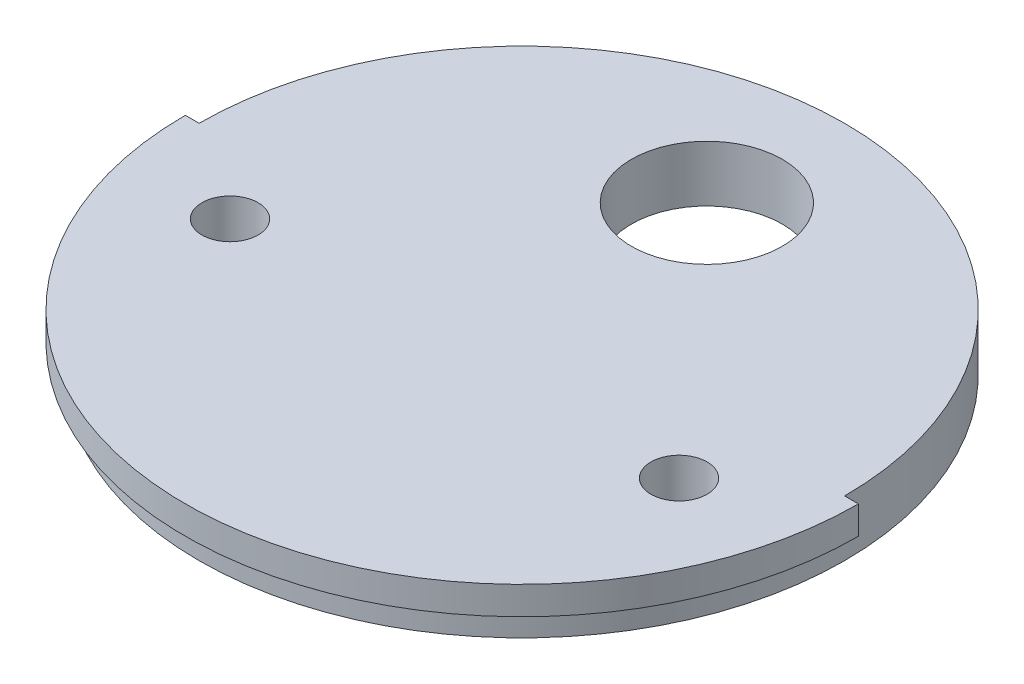
SolidWorks part; units mm, degrees
ref_plane "Front Plane" through (0, 0, 0) normal (0, 0, 1) x (1, 0, 0)
ref_plane "Top Plane" through (0, 0, 0) normal (0, 1, 0) x (1, 0, 0)
ref_plane "Right Plane" through (0, 0, 0) normal (1, 0, 0) x (0, 0, -1)
sketch "Sketch1" plane through (0, 0, 0) normal (0, 1, 0) x (1, 0, 0)
  circle A0 centre (0, 0) radius 36.5125
  dimension "D1" = 73.025
extrude "Boss-Extrude1" add sketch "Sketch1" along normal blind 3.175
sketch "Sketch2" plane through (0, 3.175, 0) normal (0, 1, 0) x (1, 0, 0)
  circle A0 centre (0, 0) radius 38.0746
  dimension "D1" = 76.1492
extrude "Boss-Extrude2" add sketch "Sketch2" along normal blind 3.175
sketch "Sketch3" plane through (0, 0, 0) normal (0, -1, 0) x (1, 0, 0)
  circle A0 centre (0, -20.9296) radius 13.97 construction
  circle A1 centre (0, 0) radius 36.5125 construction
  circle A2 centre (0, 0) radius 36.5125 construction
  circle A3 centre (0, -20.9296) radius 5.08
  circle A4 centre (0, 0) radius 38.0746 construction
  point P2 (0, -36.5125)
  point P4 (0, -34.8996)
  point P5 (0, -38.0746)
  dimension "D1" = 27.94
  dimension "D3" = 10.16
  dimension "D2" = 3.175
extrude "Cut-Extrude1" cut sketch "Sketch3" against normal through all
sketch "Sketch4" [suppressed] plane through (0, 0, 0) normal (0, -1, 0) x (1, 0, 0)
  circle A2 centre (0, -20.9296) radius 5.08 construction
  circle A3 centre (0, 7.0104) radius 15.24 construction
  circle A4 centre (0, -20.9296) radius 12.7 construction
  circle A5 centre (0, 7.0104) radius 11.43
  circle A6 centre (-14, 21.0104) radius 1.4999
  circle A7 centre (14, 21.0104) radius 1.4999
  circle A8 centre (14, -6.9896) radius 1.4999
  circle A9 centre (-14, -6.9896) radius 1.4999
  circle A10 centre (0, 0) radius 36.5125 construction
  circle A11 centre (0, 0) radius 36.5125 construction
  point P16 (0, 22.2504)
  point P17 (0, 36.5125)
  dimension "D1" = 22.86
  dimension "D2" = 2.9997
  dimension "D3" = 30.48
  dimension "D4" = 25.4
  dimension "D5" = 28
  dimension "D6" = 27.94
  dimension "D7" = 28
  dimension "D8" = 14
  dimension "D9" = 14
extrude "Cut-Extrude2" [suppressed] cut sketch "Sketch4" against normal through all
sketch "Sketch5" [suppressed] plane through (0, 0, 0) normal (0, -1, 0) x (1, 0, 0)
  circle A0 centre (0, -20.6375) radius 13.97
  circle A1 centre (0, 7.3025) radius 16.51
  circle A2 centre (0, -20.6375) radius 5.08 construction
  dimension "D1" = 27.94
  dimension "D2" = 33.02
  dimension "D3" = 27.94
sketch "Sketch6" [suppressed] plane through (0, 0, 0) normal (0, -1, 0) x (1, 0, 0)
  circle A0 centre (-25.4, 0) radius 3.175
  circle A1 centre (25.4, 0) radius 3.175
  dimension "D1" = 50.8
  dimension "D3" = 6.35
  dimension "D2" = 25.4
extrude "Cut-Extrude3" [suppressed] cut sketch "Sketch6" against normal through all
sketch "Sketch7" plane through (0, 6.35, 0) normal (0, 1, 0) x (1, 0, 0)
  circle A0 centre (-25.4, 0) radius 3.175
  circle A1 centre (25.4, 0) radius 3.175
  dimension "D1" = 6.35
  dimension "D2" = 25.4
  dimension "D3" = 50.8
extrude "Cut-Extrude4" cut sketch "Sketch7" against normal through all
sketch "Sketch8" plane through (0, 0, 0) normal (0, -1, 0) x (1, 0, 0)
  line L0 (-38.0746, 0) -> (-36.5125, 0)
  line L1 (38.0746, 0) -> (36.5125, 0)
  circle A0 centre (0, -20.9296) radius 8.5344
  arc A1 (-38.0746, 0) -> (38.0746, 0) centre (0, 0) ccw
  arc A2 (-36.5125, 0) -> (36.5125, 0) centre (0, 0) ccw
  dimension "D1" = 17.0688
  dimension "D2" = 76.1492
  dimension "D3" = 73.025
extrude "Cut-Extrude5" cut sketch "Sketch8" against normal through all
sketch "Sketch9" plane through (0, 0, 0) normal (0, -1, 0) x (1, 0, 0)
  circle A0 centre (-25.4, 0) radius 3.175
  circle A1 centre (25.4, 0) radius 3.175
extrude "Boss-Extrude3" add sketch "Sketch9" against normal up to surface (6.35 mm away) up to face at (0, 6.35, 0.3905)
sketch "Sketch10" plane through (0, 0, 0) normal (0, -1, 0) x (1, 0, 0)
  circle A0 centre (-25.4, 7.62) radius 3.175
  circle A1 centre (25.4, 7.62) radius 3.175
  dimension "D1" = 6.35
  dimension "D2" = 6.35
  dimension "D3" = 50.8
  dimension "D4" = 25.4
  dimension "D5" = 7.62
extrude "Cut-Extrude6" cut sketch "Sketch10" against normal through all
sketch "Sketch11" [suppressed] plane through (0, 6.35, 0) normal (0, 1, 0) x (1, 0, 0)
  circle A0 centre (-25.4, 0) radius 3.175
  circle A1 centre (25.4, 0) radius 3.175
extrude "Boss-Extrude4" [suppressed] add sketch "Sketch11" against normal up to surface (6.35 mm away)
sketch "Sketch12" [suppressed] plane through (0, 6.35, 0) normal (0, 1, 0) x (1, 0, 0)
  circle A0 centre (-25.4, -7.62) radius 3.175
  circle A1 centre (25.4, -7.62) radius 3.175
  dimension "D1" = 6.35
  dimension "D2" = 6.35
  dimension "D3" = 50.8
  dimension "D4" = 25.4
  dimension "D5" = 7.62
extrude "Cut-Extrude7" [suppressed] cut sketch "Sketch12" against normal through all
